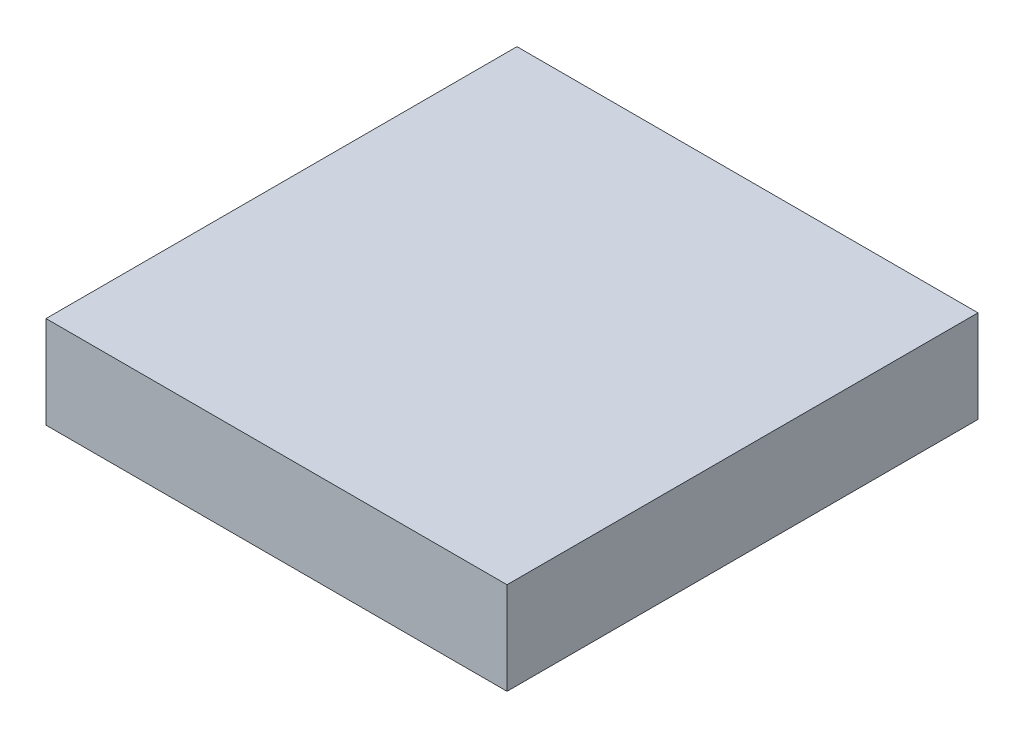
SolidWorks part; units mm, degrees
ref_plane "Front Plane" through (0, 0, 0) normal (0, 0, 1) x (1, 0, 0)
ref_plane "Top Plane" through (0, 0, 0) normal (0, 1, 0) x (1, 0, 0)
ref_plane "Right Plane" through (0, 0, 0) normal (1, 0, 0) x (0, 0, -1)
sketch "Sketch1" plane through (0, 0, 0) normal (0, 1, 0) x (1, 0, 0)
  line L5 (-60.5, -10.2) -> (-40.5302, -10.2)
  line L15 (-60.5, 10.2) -> (-40.5302, 10.2)
  line L16 (-60.5, 10.2) -> (-60.5, -10.2)
  line L18 (-40.5302, 10.2) -> (-40.5302, -10.2)
  dimension "D1" = 19.9698
  dimension "D2" = 20.4
extrude "Boss-Extrude1" add sketch "Sketch1" along normal mid plane 4
